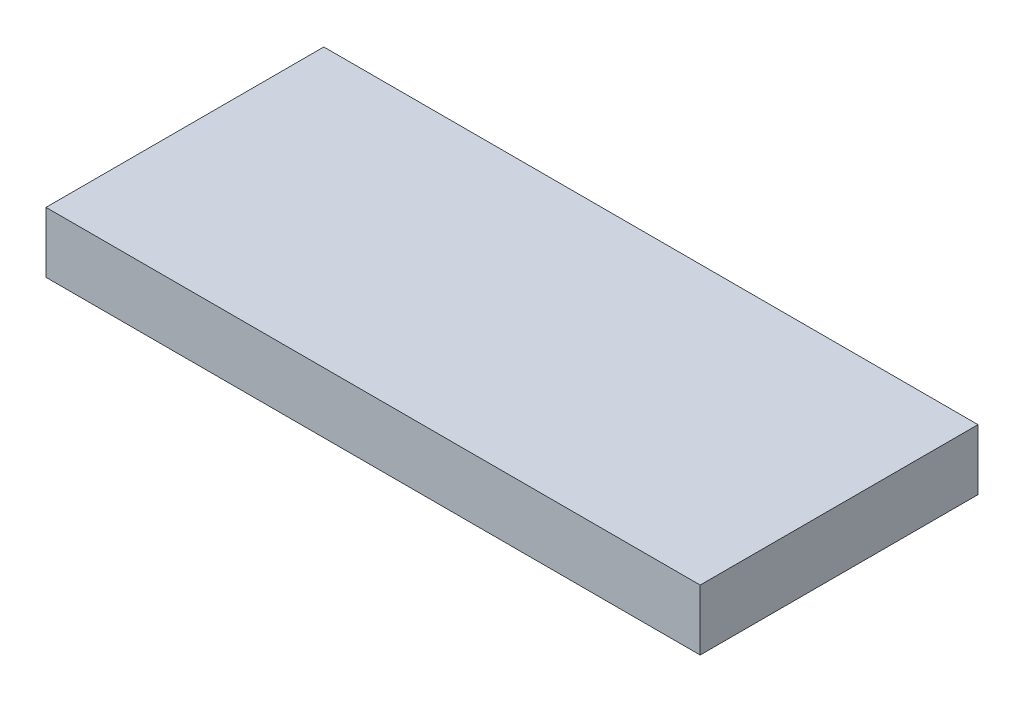
SolidWorks part; units mm, degrees
ref_plane "Front Plane" through (0, 0, 0) normal (0, 0, 1) x (1, 0, 0)
ref_plane "Top Plane" through (0, 0, 0) normal (0, 1, 0) x (1, 0, 0)
ref_plane "Right Plane" through (0, 0, 0) normal (1, 0, 0) x (0, 0, -1)
sketch "Sketch1" plane through (0, 0, 0) normal (0, 1, 0) x (1, 0, 0)
  line L1 (0, 0) -> (89.55, 0)
  line L2 (0, 0) -> (0, 38.033)
  line L3 (0, 38.033) -> (89.55, 38.033)
  line L4 (89.55, 0) -> (89.55, 38.033)
  dimension "D1" = 89.55
  dimension "D2" = 38.033
extrude "Boss-Extrude1" add sketch "Sketch1" along normal blind 8.3
